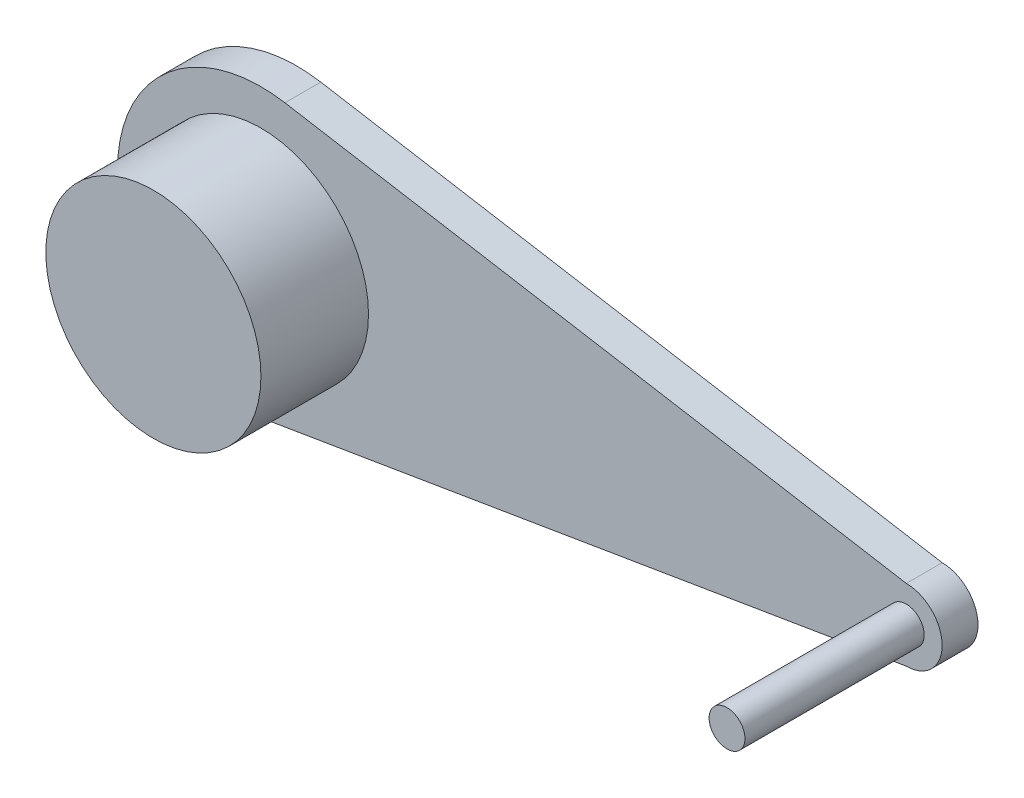
SolidWorks part; units mm, degrees
ref_plane "Front Plane" through (0, 0, 0) normal (0, 0, 1) x (1, 0, 0)
ref_plane "Top Plane" through (0, 0, 0) normal (0, 1, 0) x (1, 0, 0)
ref_plane "Right Plane" through (0, 0, 0) normal (1, 0, 0) x (0, 0, -1)
sketch "Sketch1" plane through (0, 0, 0) normal (0, 0, 1) x (1, 0, 0)
  line L0 (18, 1) -> (0.6698, 3.9435)
  line L1 (18, -1) -> (0, -4)
  arc A0 (0.6698, 3.9435) -> (0, -4) centre (0, 0) ccw
  arc A1 (18, -1) -> (18, 1) centre (18, 0) ccw
  dimension "D1" = 8
  dimension "D2" = 2
  dimension "D3" = 18
extrude "Boss-Extrude1" add sketch "Sketch1" along normal blind 1
sketch "Sketch2" plane through (0, 0, 1) normal (0, 0, 1) x (1, 0, 0)
  circle A0 centre (18, 0) radius 0.5
  circle A1 centre (0, 0) radius 3
  dimension "D1" = 6
  dimension "D2" = 1
extrude "Boss-Extrude2" add sketch "Sketch2" along normal blind 3
sketch "Sketch3" plane through (0, 0, 4) normal (0, 0, 1) x (1, 0, 0)
  circle A0 centre (18, 0) radius 0.5
extrude "Boss-Extrude3" add sketch "Sketch3" along normal blind 2
